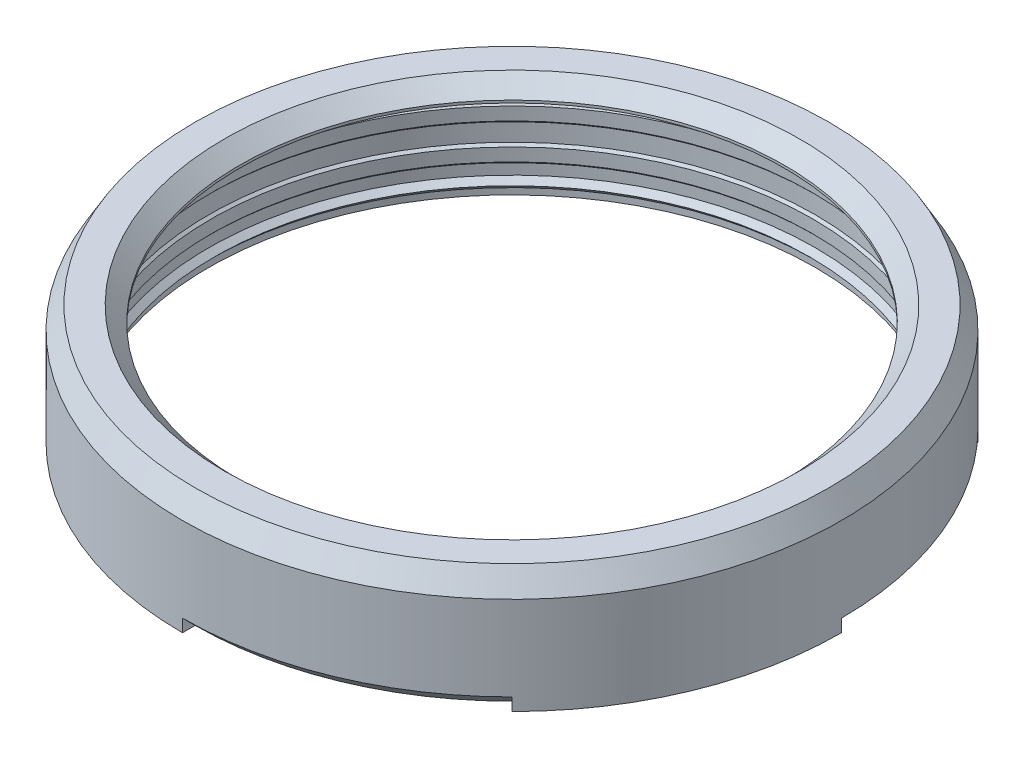
SolidWorks part; units mm, degrees
ref_plane "前视基准面" through (0, 0, 0) normal (0, 0, 1) x (1, 0, 0)
ref_plane "上视基准面" through (0, 0, 0) normal (0, 1, 0) x (1, 0, 0)
ref_plane "右视基准面" through (0, 0, 0) normal (1, 0, 0) x (0, 0, -1)
sketch "草图1" plane through (0, 0, 0) normal (0, 1, 0) x (1, 0, 0)
  circle A0 centre (0, 0) radius 26
  dimension "D1" = 52
extrude "凸台-拉伸1" add sketch "草图1" along normal blind 2
sketch "草图4" plane through (0, 0, 0) normal (-0.5, 0, 0.866) x (0.866, 0, 0.5)
  line L0 (23.93, -8) -> (23.93, -7.5)
  line L1 (23.93, -7.5) -> (23.505, -7.075)
  line L2 (23.505, -7.075) -> (23.93, -6.65)
  line L3 (23.93, -6.65) -> (23.93, -5.8)
  line L4 (23.93, -5.8) -> (23.74, -5.61)
  line L5 (23.74, -5.61) -> (23.74, -4.59)
  line L6 (23.74, -4.59) -> (23.93, -4.4)
  line L7 (23.93, -4.4) -> (23.93, -3)
  line L8 (23.93, -3) -> (23.74, -2.81)
  line L9 (23.74, -2.81) -> (23.74, -1.79)
  line L10 (23.74, -1.79) -> (23.93, -1.6)
  line L11 (23.93, -1.6) -> (23.93, -1.4)
  line L12 (22.53, 0) -> (26, 0)
  line L13 (26, 0) -> (26, -8)
  line L14 (26, -8) -> (23.93, -8)
  line L15 (23.8, -8) -> (25, -8) construction
  line L16 (23.8, -8) -> (23.8, -7.5) construction
  line L17 (0, 0) -> (0, 11.0446) construction
  arc A0 (23.93, -1.4) -> (22.53, 0) centre (22.53, -1.4) ccw
  dimension "D9" = 1.4
  dimension "D1" = 2.26
  dimension "D2" = 8
  dimension "D3" = 0.5
  dimension "D4" = 0.85
  dimension "D5" = 1.4
  dimension "D6" = 1.02
  dimension "D7" = 1.02
  dimension "D8" = 0.2
  dimension "D10" = 135
  dimension "D11" = 0.13
revolve "旋转1" add sketch "草图4" angle 360 about L17
sketch "草图5" plane through (0, 2, 0) normal (0, 1, 0) x (1, 0, 0)
  circle A0 centre (0, 0) radius 21.5
  circle A1 centre (0, 0) radius 26 construction
  dimension "D1" = 4.5
extrude "切除-拉伸1" cut sketch "草图5" against normal through all
sketch "草图7" plane through (0, 2, 0) normal (0, 1, 0) x (1, 0, 0)
  circle A1 centre (0, 0) radius 26
  circle A2 centre (0, 0) radius 26
  dimension "D1" = 0
extrude "切除-拉伸2" cut sketch "草图7" against normal blind 0.6
chamfer "倒角1" distance 1.732 angle 30 1 edges at (0, 1.4, 26)
chamfer "倒角2" distance 1.2 angle 45 1 edges at (0, 1.4, 21.5)
sketch "草图8" plane through (0, 0, 0) normal (0, 0, 1) x (1, 0, 0)
  line L0 (26, -8) -> (26, -7)
  line L1 (26, -8) -> (26, -0.332) construction
  line L2 (26, -7) -> (25, -8)
  line L3 (11.391, -8) -> (38.2611, -8) construction
  line L4 (25, -8) -> (26, -8)
  line L5 (0, 0) -> (0, 3.8102) construction
  dimension "D1" = 1
  dimension "D2" = 1
revolve "切除-旋转1" cut sketch "草图8" angle 45 about L5
pattern_circular "阵列(圆周)1" count 4 over 360 about axis through (0, 0, 0) along (0, 1, 0) of "切除-旋转1"
sketch "草图9" plane through (0, 0, 0) normal (0, -1, 0) x (1, 0, 0)
  circle A0 centre (0, 0) radius 22.32
  circle A1 centre (0, 0) radius 22.78
  circle A2 centre (0, 0) radius 21.5 construction
  dimension "D1" = 0.82
  dimension "D2" = 0.46
extrude "凸台-拉伸2" add sketch "草图9" along normal blind 0.5
